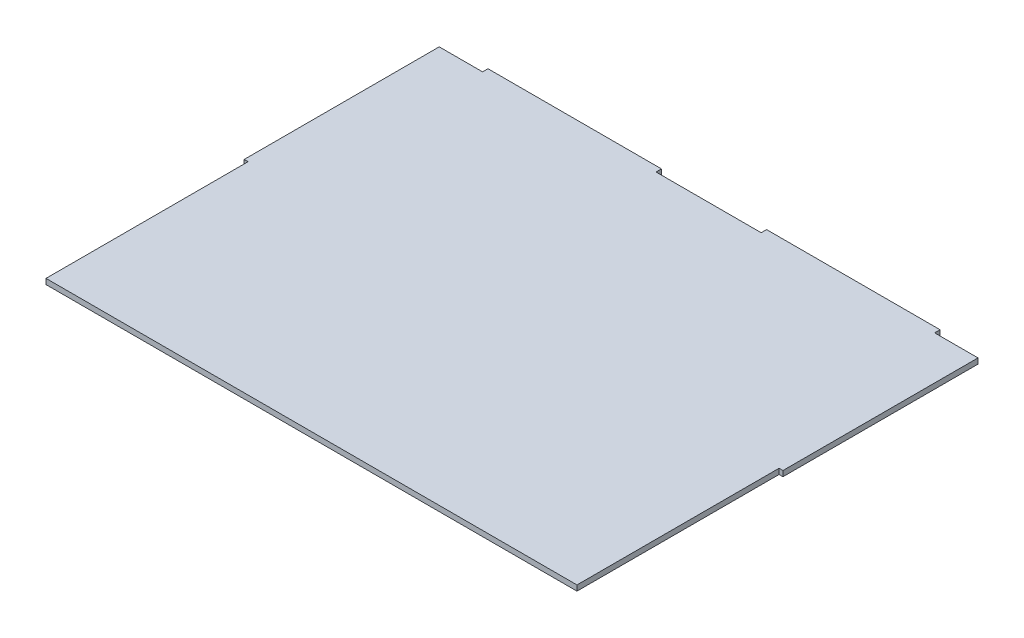
SolidWorks part; units mm, degrees
material "Custom Plastic"
ref_plane "X-Y Datum" through (0, 0, 0) normal (0, 0, 1) x (1, 0, 0)
ref_plane "X-Z Datum" through (0, 0, 0) normal (0, 1, 0) x (1, 0, 0)
ref_plane "Y-Z Datum" through (0, 0, 0) normal (1, 0, 0) x (0, 0, -1)
sketch "Sketch1" plane through (0, 0, 0) normal (0, 0, 1) x (1, 0, 0)
  line L1 (-157.7875, -1.5875) -> (157.7875, -1.5875)
  line L2 (-157.7875, -1.5875) -> (-157.7875, 1.5875)
  line L3 (-157.7875, 1.5875) -> (157.7875, 1.5875)
  line L4 (157.7875, -1.5875) -> (157.7875, 1.5875)
  line L5 (-157.7875, -1.5875) -> (157.7875, 1.5875) construction
  line L6 (-157.7875, 1.5875) -> (157.7875, -1.5875) construction
  point P0 (0, 0)
  dimension "D1" = 315.575
  dimension "D2" = 3.175
extrude "Boss-Extrude1" add sketch "Sketch1" along normal blind 235.775
sketch "Sketch3" plane through (0, 0, 0) normal (0, 0, -1) x (-1, 0, 0)
  line L0 (-157.7875, 0) -> (-81.5875, 0) construction
  line L1 (-157.7875, -1.5875) -> (-157.7875, 1.5875) construction
  line L2 (-157.7875, 1.5875) -> (157.7875, 1.5875) construction
  line L3 (-132.3875, -1.5875) -> (-30.7875, -1.5875)
  line L4 (-132.3875, -1.5875) -> (-132.3875, 1.5875)
  line L5 (-132.3875, 1.5875) -> (-30.7875, 1.5875)
  line L6 (-30.7875, -1.5875) -> (-30.7875, 1.5875)
  line L7 (-132.3875, -1.5875) -> (-30.7875, 1.5875) construction
  line L8 (-132.3875, 1.5875) -> (-30.7875, -1.5875) construction
  line L14 (-157.7875, 1.5875) -> (-132.3875, 1.5875)
  line L15 (-157.7875, 1.5875) -> (-157.7875, -1.5875)
  line L16 (-157.7875, -1.5875) -> (-132.3875, -1.5875)
  line L17 (-132.3875, 1.5875) -> (-132.3875, -1.5875)
  line L19 (-30.7875, 1.5875) -> (-30.7875, -1.5875)
  line L20 (0, 43.0151) -> (0, -43.0151) construction
  line L21 (30.7875, -1.5875) -> (30.7875, 1.5875)
  line L22 (132.3875, -1.5875) -> (132.3875, 1.5875)
  line L23 (132.3875, 1.5875) -> (30.7875, 1.5875)
  line L24 (132.3875, -1.5875) -> (30.7875, 1.5875) construction
  line L25 (132.3875, -1.5875) -> (30.7875, -1.5875)
  line L26 (132.3875, 1.5875) -> (30.7875, -1.5875) construction
  dimension "D1" = 76.2
  dimension "D2" = 101.6
extrude "Cut-Extrude1" cut sketch "Sketch3" against normal blind 3.175
sketch "Sketch5" plane through (0, 1.5875, 0) normal (0, 1, 0) x (1, 0, 0)
  line L1 (-157.7875, -235.775) -> (-155.5015, -235.775)
  line L3 (-157.7875, -235.775) -> (-157.7875, -117.411)
  line L5 (-157.7875, -117.411) -> (-155.5015, -117.411)
  line L6 (-155.5015, -235.775) -> (-155.5015, -117.411)
  dimension "D1" = 118.364
  dimension "D2" = 2.286
extrude "Cut-Extrude2" cut sketch "Sketch5" against normal blind 3.175 and the other way through all
mirror "Mirror1" about plane through (0, 0, 0) normal (1, 0, 0) of "Cut-Extrude2"
sketch "Sketch6" plane through (0, 1.5875, 0) normal (0, 1, 0) x (1, 0, 0)
  line L0 (-157.79, -235.775) -> (-157.79, -134.175) construction
  line L5 (155.5015, -235.775) -> (-155.5015, -235.775) construction
  line L8 (-157.79, -235.775) -> (-73.389, -235.775)
  line L10 (-157.79, -215.455) -> (-81.59, -215.455)
  line L11 (-157.79, -215.455) -> (-157.79, -235.775)
  line L12 (-157.79, -235.775) -> (-81.59, -235.775)
  line L13 (-81.59, -215.455) -> (-81.59, -235.775)
  line M19 (-155.5015, -235.775) -> (155.5015, -235.775)
  dimension "D1" = 76.2
  dimension "D2" = 20.32
extrude "Cut-Extrude4" [suppressed] cut sketch "Sketch6" against normal through all contours L13 L10 L11 M19
mirror "Mirror2" [suppressed] about plane through (0, 0, 0) normal (1, 0, 0)
